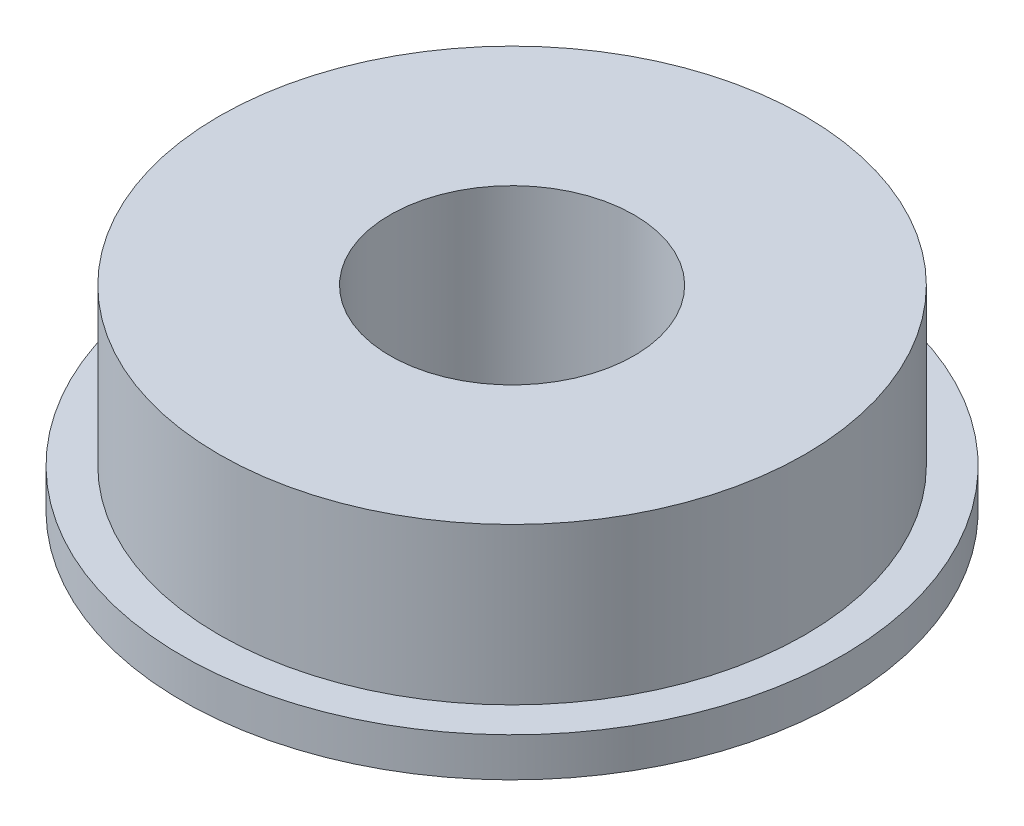
SolidWorks part; units mm, degrees
ref_plane "Front Plane" through (0, 0, 0) normal (0, 0, 1) x (1, 0, 0)
ref_plane "Top Plane" through (0, 0, 0) normal (0, 1, 0) x (1, 0, 0)
ref_plane "Right Plane" through (0, 0, 0) normal (1, 0, 0) x (0, 0, -1)
sketch "Sketch1" plane through (0, 0, 0) normal (0, 0, 1) x (1, 0, 0)
  line L0 (2.5, 0) -> (2.5, 4)
  line L1 (2.5, 4) -> (6, 4)
  line L2 (6, 4) -> (6, 0.8)
  line L3 (6, 0.8) -> (6.75, 0.8)
  line L4 (6.75, 0.8) -> (6.75, 0)
  line L5 (6.75, 0) -> (2.5, 0)
  line L6 (0, 0) -> (0, 4) construction
  dimension "D1" = 4
  dimension "D2" = 3.2
  dimension "D3" = 2.5
  dimension "D4" = 6.75
  dimension "D5" = 6
revolve "Revolve1" add sketch "Sketch1" angle 360 about L6
